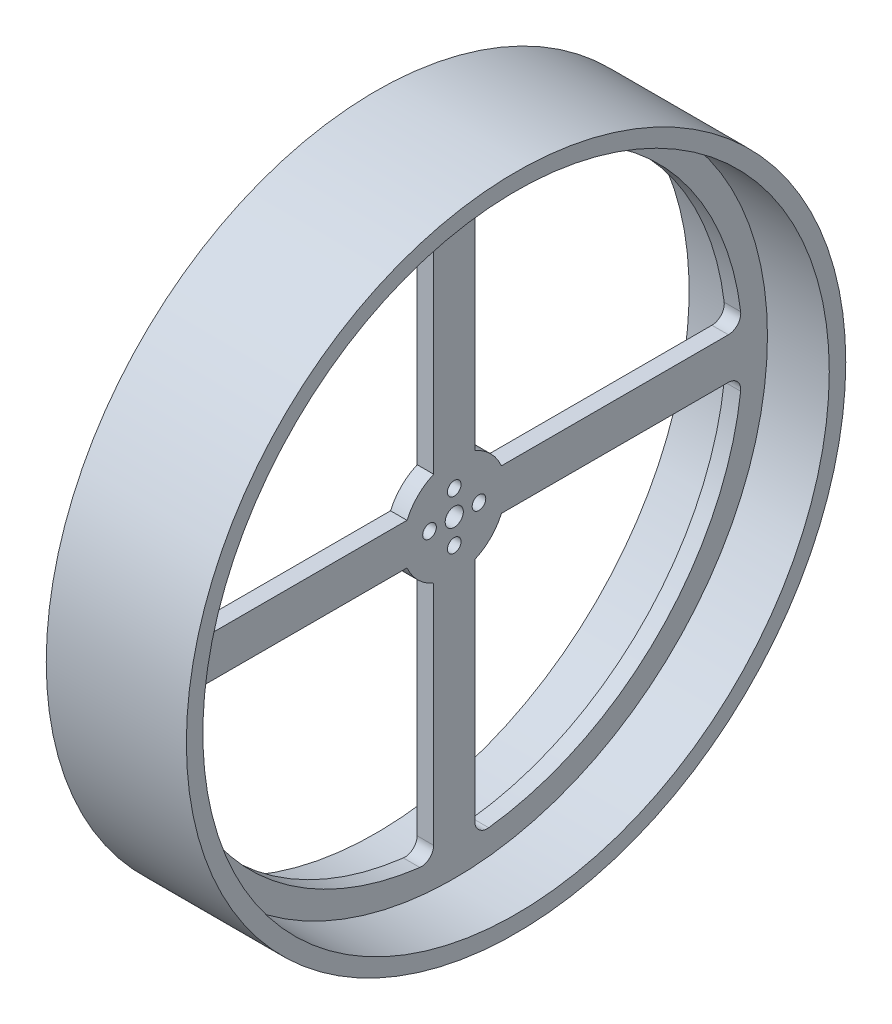
SolidWorks part; units mm, degrees
ref_plane "Front Plane" through (0, 0, 0) normal (1, 0, 0) x (0, 1, 0)
ref_plane "Top Plane" through (0, 0, 0) normal (0, 0, 1) x (0, 1, 0)
ref_plane "Right Plane" through (0, 0, 0) normal (0, 1, 0) x (-1, 0, 0)
sketch "Sketch3" plane through (0, 0, 0) normal (1, 0, 0) x (0, 1, 0)
  circle A0 centre (0, 0) radius 80
  dimension "D1" = 160
extrude "Boss-Extrude3" add sketch "Sketch3" along normal blind 4
sketch "Sketch5" plane through (4, 0, 0) normal (1, 0, 0) x (0, 1, 0)
  circle A0 centre (0, 6) radius 1.65
  circle A1 centre (6, 0) radius 1.65
  circle A2 centre (0, -6) radius 1.65
  circle A3 centre (-6, 0) radius 1.65
  point P12 (0, 0)
  dimension "D1" = 3.3
  dimension "D2" = 6
  dimension "D3" = 4
extrude "Cut-Extrude3" cut sketch "Sketch5" against normal through all
sketch "Sketch6" plane through (4, 0, 0) normal (1, 0, 0) x (0, 1, 0)
  line L0 (11.4564, 5) -> (69.8212, 5)
  line L1 (5, 11.4564) -> (5, 69.8212)
  arc A0 (5, 69.8212) -> (69.8212, 5) centre (0, 0) cw
  arc A1 (5, 11.4564) -> (11.4564, 5) centre (0, 0) cw
  dimension "D1" = 70
  dimension "D4" = 12.5
  dimension "D2" = 5
  dimension "D3" = 5
extrude "Cut-Extrude4" cut sketch "Sketch6" against normal through all
pattern_circular "CirPattern2" count 4 over 360 about axis through (0, 0, 0) along (1, 0, 0) of "Cut-Extrude4"
fillet "Fillet2" radius 3 8 edges at (2, -5, 69.8212) (2, 5, 69.8212) (2, -69.8212, 5) (2, -69.8212, -5) (2, -5, -69.8212) (2, 5, -69.8212) (2, 69.8212, -5) (2, 69.8212, 5)
sketch "Sketch7" plane through (0, 0, 0) normal (-1, 0, 0) x (0, -1, 0)
  circle A0 centre (0, 0) radius 80
  circle A1 centre (0, 0) radius 80 construction
  circle A2 centre (0, 0) radius 76
  dimension "D1" = 4
extrude "Boss-Extrude4" add sketch "Sketch7" along normal blind 15
sketch "Sketch8" plane through (4, 0, 0) normal (1, 0, 0) x (0, 1, 0)
  circle A0 centre (0, 0) radius 2.2
  dimension "D1" = 4.4
extrude "Cut-Extrude5" cut sketch "Sketch8" against normal through all
sketch "Sketch9" plane through (4, 0, 0) normal (1, 0, 0) x (0, 1, 0)
  circle A0 centre (0, 0) radius 80
  circle A1 centre (0, 0) radius 76
  circle A2 centre (0, 0) radius 80 construction
  dimension "D1" = 4
extrude "Boss-Extrude5" add sketch "Sketch9" along normal blind 15
